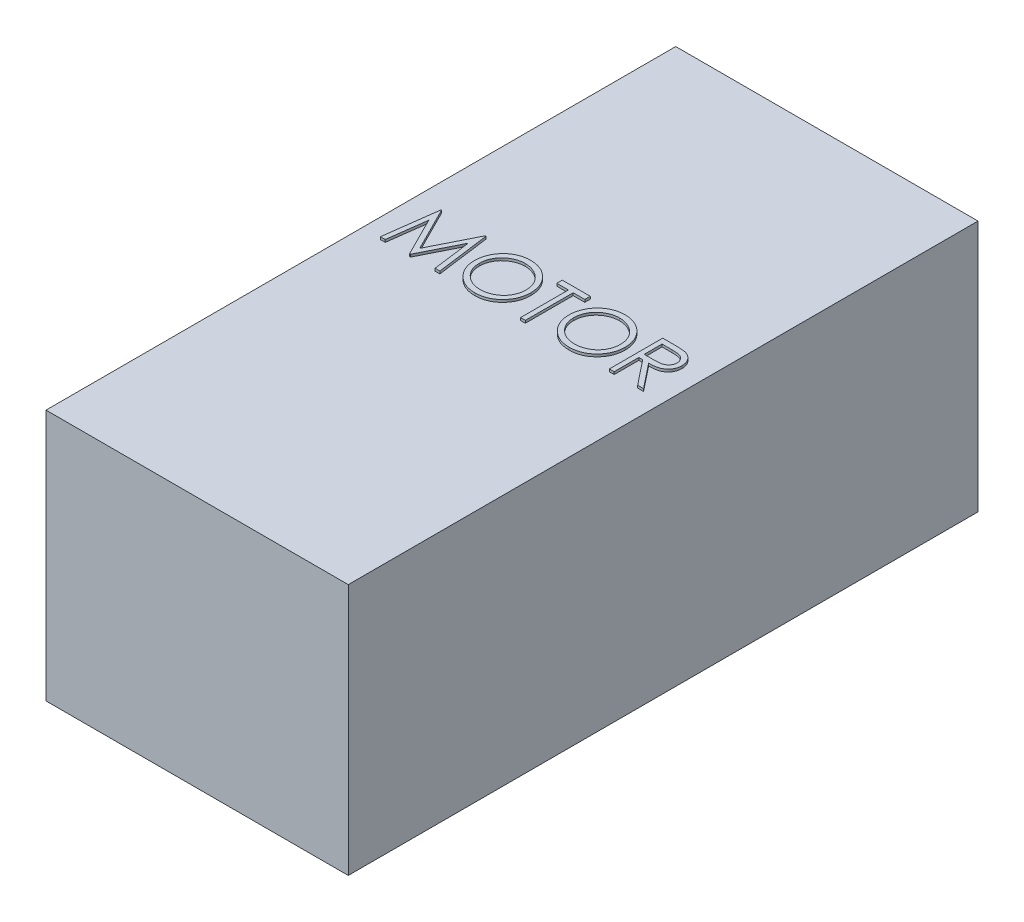
SolidWorks part; units mm, degrees
ref_plane "Front Plane" through (0, 0, 0) normal (0, 0, 1) x (1, 0, 0)
ref_plane "Top Plane" through (0, 0, 0) normal (0, 1, 0) x (1, 0, 0)
ref_plane "Right Plane" through (0, 0, 0) normal (1, 0, 0) x (0, 0, -1)
sketch "Sketch1" plane through (0, 0, 0) normal (0, 0, 1) x (1, 0, 0)
  line L1 (0, 0) -> (12, 0)
  line L2 (0, 0) -> (0, 10)
  line L3 (0, 10) -> (12, 10)
  line L4 (12, 0) -> (12, 10)
  dimension "D1" = 10
  dimension "D2" = 12
extrude "Boss-Extrude1" add sketch "Sketch1" along normal blind 25
sketch "Sketch3" plane through (0, 10, 0) normal (0, 1, 0) x (1, 0, 0)
  line L0 (0, -12.5) -> (12, -12.5) construction
  line L1 (0, -25) -> (0, 0) construction
  line L2 (12, -25) -> (12, 0) construction
  text T0 "MOTOR" font "Century Gothic" height in points 8
extrude "Boss-Extrude2" add sketch "Sketch3" along normal blind 0.1
sketch "Sketch4" plane through (0, 0, 0) normal (0, 0, -1) x (-1, 0, 0)
  line L0 (-12, 10) -> (0, 0) construction
  line L1 (-12, 0) -> (0, 10) construction
  circle A0 centre (-6, 5) radius 1.5
  dimension "D1" = 3
extrude "Cut-Extrude1" cut sketch "Sketch4" against normal blind 5
